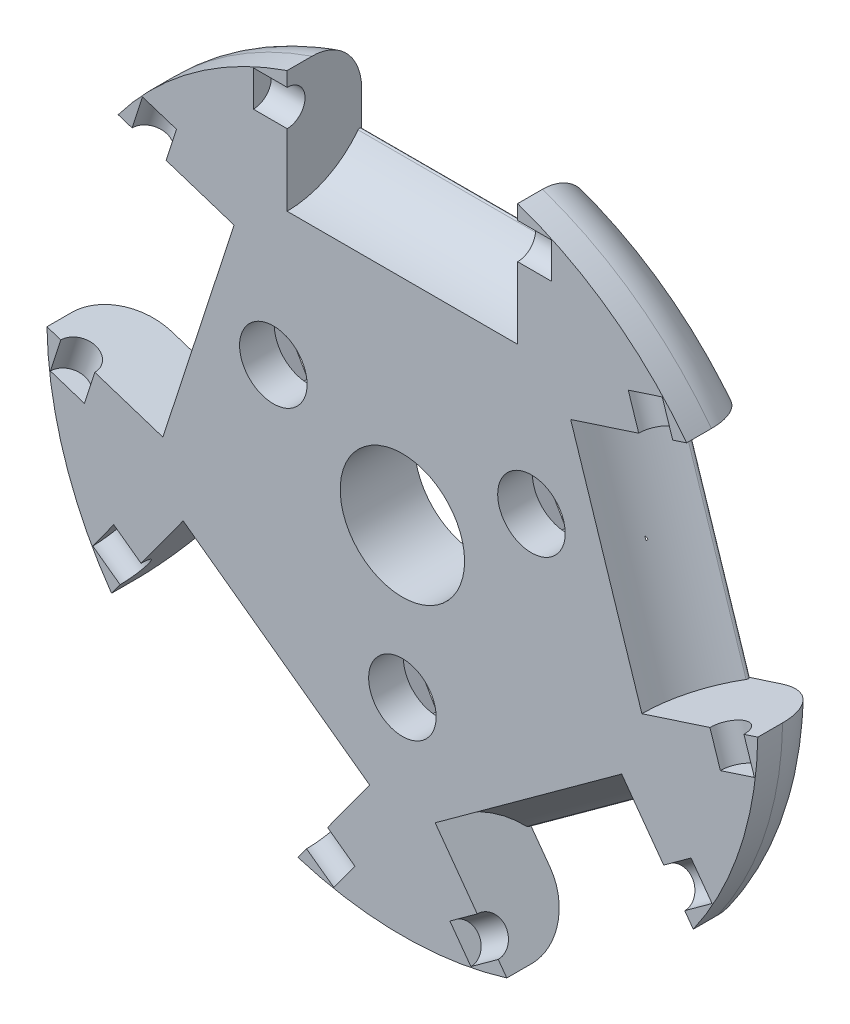
SolidWorks part; units mm, degrees
other "Markup1"
sketch "Sketch8" plane through (32.7336, 32.7336, 0) normal (0.5701, 0.1846, 0.8006) x (0.8043, 0.0736, -0.5897)
ref_plane "Front Plane" through (0, 0, 0) normal (0, 0, 1) x (1, 0, 0)
ref_plane "Top Plane" through (0, 0, 0) normal (0, 1, 0) x (1, 0, 0)
ref_plane "Right Plane" through (0, 0, 0) normal (1, 0, 0) x (0, 0, -1)
sketch "Sketch1" plane through (0, 0, 0) normal (0, 0, 1) x (1, 0, 0)
  circle A0 centre (0, 0) radius 22.7203
  dimension "D1" = 45.4406
extrude "Boss-Extrude2" add sketch "Sketch1" against normal blind 4.7625
fillet "Fillet1" radius 3.175 1 edges at (22.7203, 0, -4.7625)
sketch "Sketch2" plane through (0, 0, 0) normal (0, 0, 1) x (1, 0, 0)
  line L1 (-12.7, 22.7203) -> (12.7, 22.7203) construction
  line L2 (-7.366, 23.9903) -> (7.366, 23.9903)
  line L3 (-7.366, 23.9903) -> (-7.366, 13.5763)
  line L4 (-7.366, 13.5763) -> (7.366, 13.5763)
  line L5 (7.366, 23.9903) -> (7.366, 13.5763)
  line L6 (-7.366, 23.9903) -> (7.366, 13.5763) construction
  line L7 (-7.366, 13.5763) -> (7.366, 23.9903) construction
  line L35 (0, 0) -> (0, 22.7203) construction
  circle A1 centre (0, 0) radius 22.7203 construction
  point P10 (0, 18.7833)
  circle M7 centre (0, 0) radius 22.7203
  dimension "D1" = 14.732
  dimension "D2" = 10.414
  dimension "D3" = 1.27
  dimension "D4" = 25.4
extrude "Cut-Extrude2" cut sketch "Sketch2" against normal blind 12.7 contours L5 L3 L4 M7
pattern_circular "CirPattern1" count 5 over 360 about axis through (0, 0, 0) along (0, 0, 1) of "Cut-Extrude2"
ref_plane "Plane1" through (0, 0, 0) normal (1, 0, 0) x (0, 0, -1)
sketch "Sketch4" plane through (0, 0, 0) normal (1, 0, 0) x (0, 0, -1)
  line L0 (4.7625, 13.5763) -> (0, 13.5763) construction
  circle A0 centre (0, 19.4183) radius 1.143
  dimension "D1" = 2.286
  dimension "D2" = 5.842
extrude "Cut-Extrude4" cut sketch "Sketch4" against normal mid plane 19.05
pattern_circular "CirPattern2" count 5 over 360 about axis through (0, 0, 0) along (0, 0, 1) of "Cut-Extrude4"
sketch "Sketch5" plane through (0, 0, 0) normal (0, 0, 1) x (1, 0, 0)
  circle A0 centre (0, 0) radius 3.9751
  dimension "D1" = 7.9502
extrude "Cut-Extrude5" cut sketch "Sketch5" against normal through all
sketch "Sketch6" plane through (0, 0, -4.7625) normal (0, 0, -1) x (-1, 0, 0)
  circle A0 centre (0, -9.525) radius 2.159
  circle A1 centre (-8.2489, 4.7625) radius 2.159
  circle A2 centre (8.2489, 4.7625) radius 2.159
  point P9 (0, 0)
  dimension "D1" = 4.318
  dimension "D2" = 9.525
extrude "Cut-Extrude7" cut sketch "Sketch6" against normal through all
sketch "Sketch10" plane through (7.366, 0, 0) normal (-1, 0, 0) x (0, 0, 1)
  line L0 (-4.7625, 18.1042) -> (-4.7625, 13.5763) construction
  line L1 (-4.7625, 13.5763) -> (0, 13.5763)
  line L2 (-4.7625, 13.5763) -> (-4.7625, 16.2592)
  line L4 (0, 13.5763) -> (0, 13.7033)
  arc A0 (-4.7625, 16.2592) -> (0, 13.7033) centre (0, 19.4183) ccw
  dimension "D1" = 11.43
  dimension "D2" = 4.7625
extrude "Boss-Extrude4" add sketch "Sketch10" along normal up to next
fillet "Fillet2" radius 0.127 1 edges at (0, 16.2592, -4.7625)
pattern_circular "CirPattern5" count 5 over 360 of "Boss-Extrude4", "Fillet2"
sketch "Sketch7" plane through (0, 0, -4.7625) normal (0, 0, -1) x (-1, 0, 0)
  line L0 (-10.8152, 0.3175) -> (-5.6826, 0.3175)
  line L1 (5.1326, -9.525) -> (2.5663, -5.08)
  line L2 (2.5663, -5.08) -> (-2.5663, -5.08)
  line L3 (-2.5663, -5.08) -> (-5.1326, -9.525)
  line L4 (-5.1326, -9.525) -> (-2.5663, -13.97)
  line L5 (-2.5663, -13.97) -> (2.5663, -13.97)
  line L6 (2.5663, -13.97) -> (5.1326, -9.525)
  line L7 (-5.6826, 0.3175) -> (-3.1162, 4.7625)
  line L8 (-3.1162, 4.7625) -> (-5.6826, 9.2075)
  line L9 (-5.6826, 9.2075) -> (-10.8152, 9.2075)
  line L10 (-10.8152, 9.2075) -> (-13.3815, 4.7625)
  line L11 (-13.3815, 4.7625) -> (-10.8152, 0.3175)
  line L12 (5.6826, 9.2075) -> (3.1162, 4.7625)
  line L13 (3.1162, 4.7625) -> (5.6826, 0.3175)
  line L14 (5.6826, 0.3175) -> (10.8152, 0.3175)
  line L15 (10.8152, 0.3175) -> (13.3815, 4.7625)
  line L16 (13.3815, 4.7625) -> (10.8152, 9.2075)
  line L17 (10.8152, 9.2075) -> (5.6826, 9.2075)
  circle A4 centre (0, -9.525) radius 4.445 construction
  point P23 (0, 0)
  dimension "D1" = 8.89
  dimension "D2" = 5.1326
extrude "Cut-Extrude8" cut sketch "Sketch7" against normal blind 2.54
